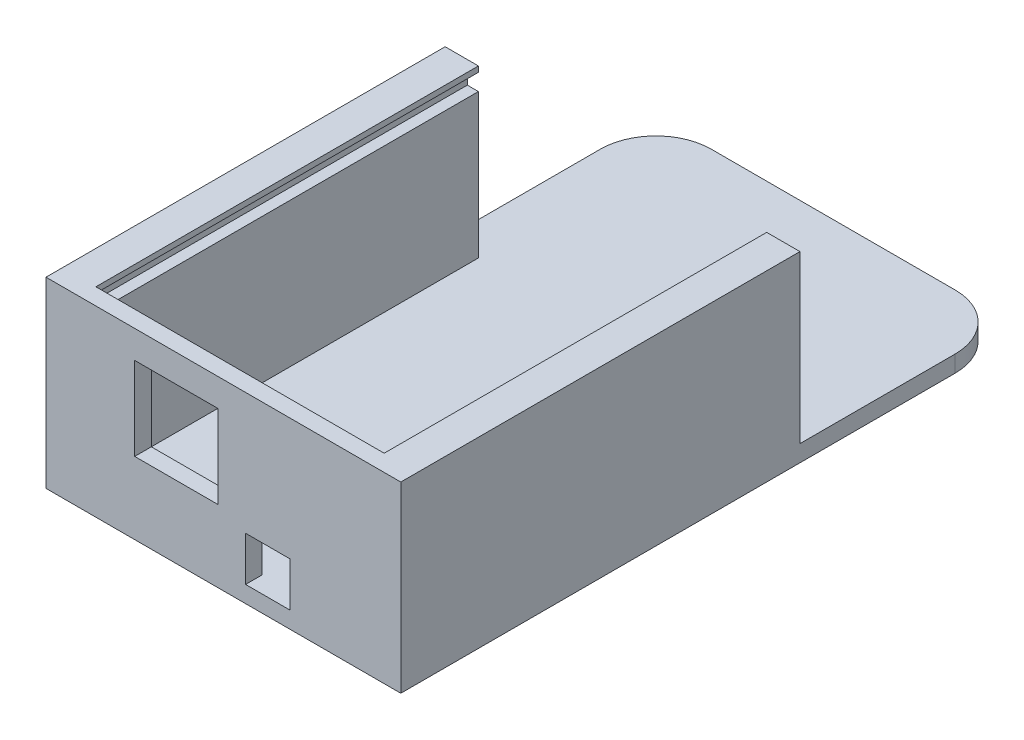
SolidWorks part; units mm, degrees
ref_plane "Front Plane" through (0, 0, 0) normal (0, 0, 1) x (1, 0, 0)
ref_plane "Top Plane" through (0, 0, 0) normal (0, 1, 0) x (1, 0, 0)
ref_plane "Right Plane" through (0, 0, 0) normal (1, 0, 0) x (0, 0, -1)
sketch "Sketch1" plane through (0, 0, 0) normal (0, 1, 0) x (1, 0, 0)
  line L1 (0, 0) -> (32, 0)
  line L2 (0, 0) -> (0, 110)
  line L3 (0, 110) -> (32, 110)
  line L4 (32, 0) -> (32, 110)
  dimension "D1" = 110
  dimension "D2" = 32
extrude "Boss-Extrude1" add sketch "Sketch1" along normal blind 3
sketch "Sketch2" plane through (0, 3, 0) normal (0, 1, 0) x (1, 0, 0)
  line L0 (32, 0) -> (32, 110) construction
  line L1 (0, 0) -> (32, 0)
  line L2 (0, 0) -> (0, 3)
  line L3 (0, 3) -> (32, 3)
  line L4 (32, 0) -> (32, 3)
  line L6 (26, 3) -> (32, 3)
  line L7 (26, 3) -> (26, 72)
  line L8 (26, 72) -> (32, 72)
  line L9 (32, 3) -> (32, 72)
  line M9 (0, 110) -> (0, 0)
  line M10 (0, 0) -> (32, 0)
  line M11 (32, 0) -> (32, 110)
  dimension "D1" = 3
  dimension "D2" = 6
  dimension "D3" = 69
extrude "Boss-Extrude2" add sketch "Sketch2" along normal blind 30 contours L3 M9 M10 M11 | L8 L7 L3 M11
sketch "Sketch3" plane through (0, 0, -72) normal (0, 0, -1) x (-1, 0, 0)
  line L0 (-26, 32) -> (-28, 30)
  line L1 (-26, 33) -> (-26, 3) construction
  line L2 (-28, 30) -> (-28, 29)
  line L3 (-28, 29) -> (-26, 29)
  line L4 (-26, 33) -> (-26, 3) construction
  line L5 (-26, 29) -> (-26, 32)
  line L6 (-26, 33) -> (-32, 33) construction
  dimension "D1" = 2
  dimension "D2" = 45
  dimension "D3" = 3
  dimension "D4" = 1
extrude "Cut-Extrude1" cut sketch "Sketch3" against normal up to surface (69 mm away) up to face at (13, 18, -3)
fillet "Fillet1" radius 10 1 edges at (32, 1.5, -110)
mirror "Mirror1" about plane through (0, 3, 0) normal (1, 0, 0) of "Fillet1", "Cut-Extrude1", "Boss-Extrude2", "Boss-Extrude1"
sketch "Sketch4" plane through (0, 0, -3) normal (0, 0, -1) x (-1, 0, 0)
  line L1 (1, 28) -> (16, 28)
  line L2 (1, 28) -> (1, 13)
  line L3 (1, 13) -> (16, 13)
  line L4 (16, 28) -> (16, 13)
  line L5 (26, 3) -> (-26, 3) construction
  line L6 (-12, 11) -> (-4, 11)
  line L7 (-12, 11) -> (-12, 3)
  line L8 (-12, 3) -> (-4, 3)
  line L9 (-4, 11) -> (-4, 3)
  line L11 (26, 33) -> (-26, 33) construction
  line L12 (26, 29) -> (26, 3) construction
  dimension "D1" = 15
  dimension "D2" = 15
  dimension "D3" = 25
  dimension "D4" = 8
  dimension "D5" = 8
  dimension "D6" = 0
  dimension "D7" = 5
  dimension "D8" = 5
extrude "Cut-Extrude2" cut sketch "Sketch4" against normal through all
